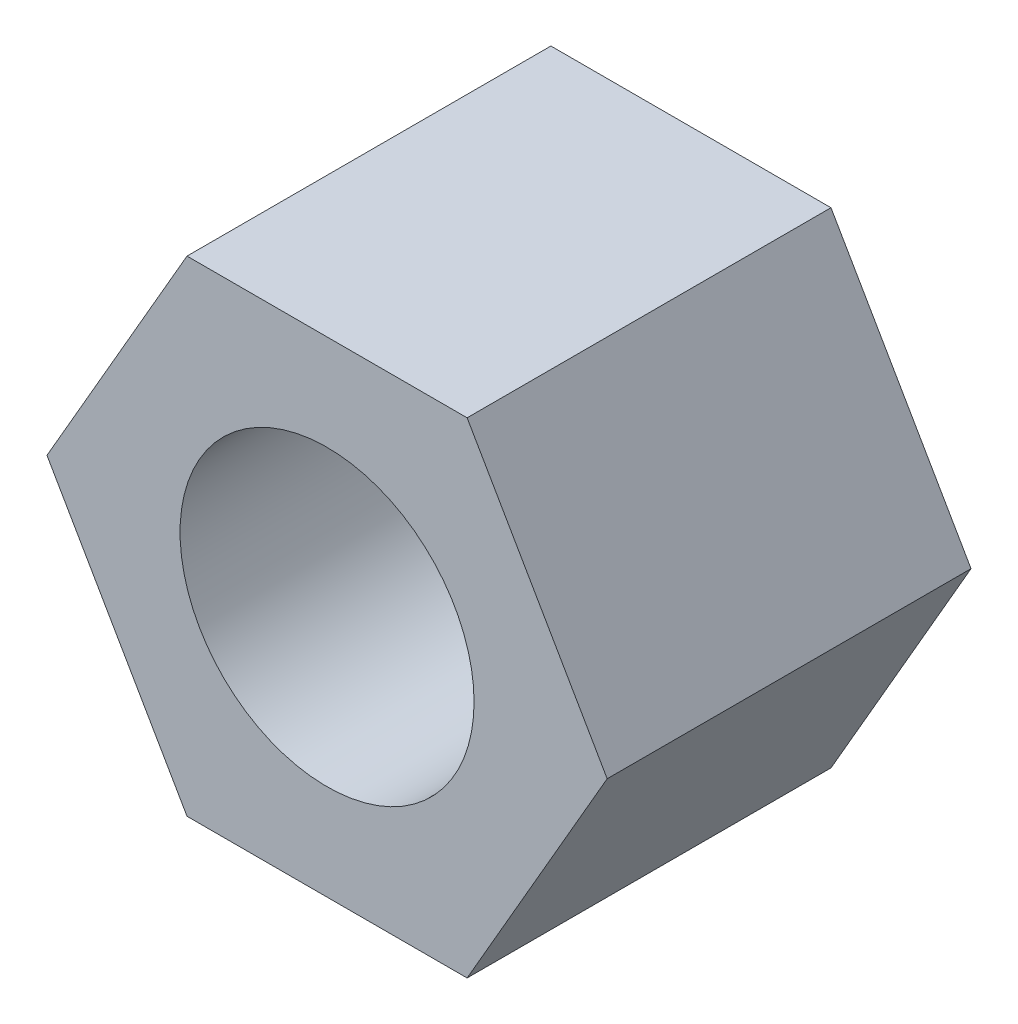
SolidWorks part; units mm, degrees
ref_plane "Front Plane" through (0, 0, 0) normal (0, 0, 1) x (1, 0, 0)
ref_plane "Top Plane" through (0, 0, 0) normal (0, 1, 0) x (1, 0, 0)
ref_plane "Right Plane" through (0, 0, 0) normal (1, 0, 0) x (0, 0, -1)
sketch "S01 - Hexagon and nominal thread envelope" plane through (0, 0, 0) normal (0, 0, 1) x (1, 0, 0)
  line L0 (5.7735, 0) -> (2.8868, 5)
  line L1 (2.8868, 5) -> (-2.8868, 5)
  line L2 (-2.8868, 5) -> (-5.7735, 0)
  line L3 (-5.7735, 0) -> (-2.8868, -5)
  line L4 (-2.8868, -5) -> (2.8868, -5)
  line L5 (2.8868, -5) -> (5.7735, 0)
  circle A0 centre (0, 0) radius 3.03
  dimension "D1" = 6.06
  dimension "D2" = 2.8868
  dimension "D3" = 5.7735
  dimension "D4" = 2.8868
  dimension "D5" = 5.7735
  dimension "D6" = 5
  dimension "D7" = 5
extrude "01 - Hexagon and nominal thread envelope" add sketch "S01 - Hexagon and nominal thread envelope" along normal blind 7.5
